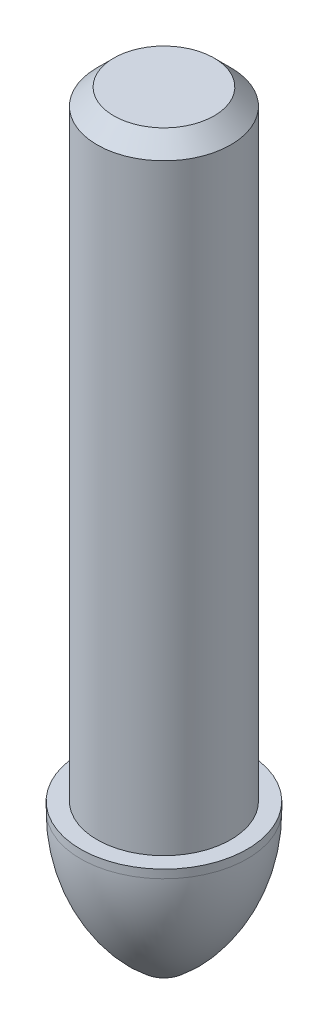
SolidWorks part; units mm, degrees
material "K110"
ref_plane "Front Plane" through (0, 0, 0) normal (0, 0, 1) x (1, 0, 0)
ref_plane "Top Plane" through (0, 0, 0) normal (0, 1, 0) x (1, 0, 0)
ref_plane "Right Plane" through (0, 0, 0) normal (1, 0, 0) x (0, 0, -1)
sketch "Sketch1" plane through (0, 0, 0) normal (0, 0, 1) x (1, 0, 0)
  line L0 (0, 0) -> (0, -51.1343) construction
  line L1 (0, 0) -> (4, 0)
  line L2 (4, 0) -> (4, -37)
  line L3 (4, -37) -> (4.985, -37)
  line L4 (4.985, -37) -> (4.985, -37.5)
  line L5 (4.985, -37.5) -> (-4.985, -37.5) construction
  line L6 (0, -45.7186) -> (0, 0)
  arc A1 (1.2509, -45.2791) -> (4.985, -37.5) centre (-4.985, -37.5) ccw
  arc A2 (0, -45.7186) -> (1.2509, -45.2791) centre (0, -43.7186) ccw
  arc A3 (0, -41.7186) -> (0, -45.7186) centre (0, -43.7186) ccw construction
  arc A4 (1.2509, -45.2791) -> (0, -41.7186) centre (0, -43.7186) ccw construction
  arc A5 (0, -46.1343) -> (1.2509, -45.2791) centre (-4.985, -37.5) ccw construction
  dimension "D6" = 2
  dimension "D1" = 9.97
  dimension "PilotDiameter" = 9.97
  dimension "D2" = 8
  dimension "D4" = 9.97
  dimension "ShankLength" = 37.5
  dimension "D3" = 0.5
  dimension "D5" = 5
revolve "Revolve1" add sketch "Sketch1" angle 360 about L0
chamfer "Chamfer1" distance 1 angle 45 1 edges at (-4, 0, 0)
cosmetic thread "Cosmetic Thread2" parameters "D1"=16, "D2"=6.619
equation "\"D4@Sketch1\" = \"PilotDiameter@Sketch1\""
equation "\"Pierce Punch Diameter\"= 10"
equation "\"PilotDiameter@Sketch1\" = \"Pierce Punch Diameter\" - 0.03 * \"Material Thickness\""
equation "\"Material Thickness\"= 1mm"
equation "\"Punch Height\"= 33mm"
equation "\"ShankLength@Sketch1\"= \"Punch Height\" + \"Thread into Punch Holder\" + \"Pilot Engagement Length\" - 6"
equation "\"Thread into Punch Holder\"= 10mm"
equation "\"Pilot Engagement Length\"= \"Material Thickness\" * 0.5"
equation "\"D3@Sketch1\"= \"Pilot Engagement Length\""
equation "\"D6@Sketch1\"= Round ( \"PilotDiameter@Sketch1\" * 0.25 )"
